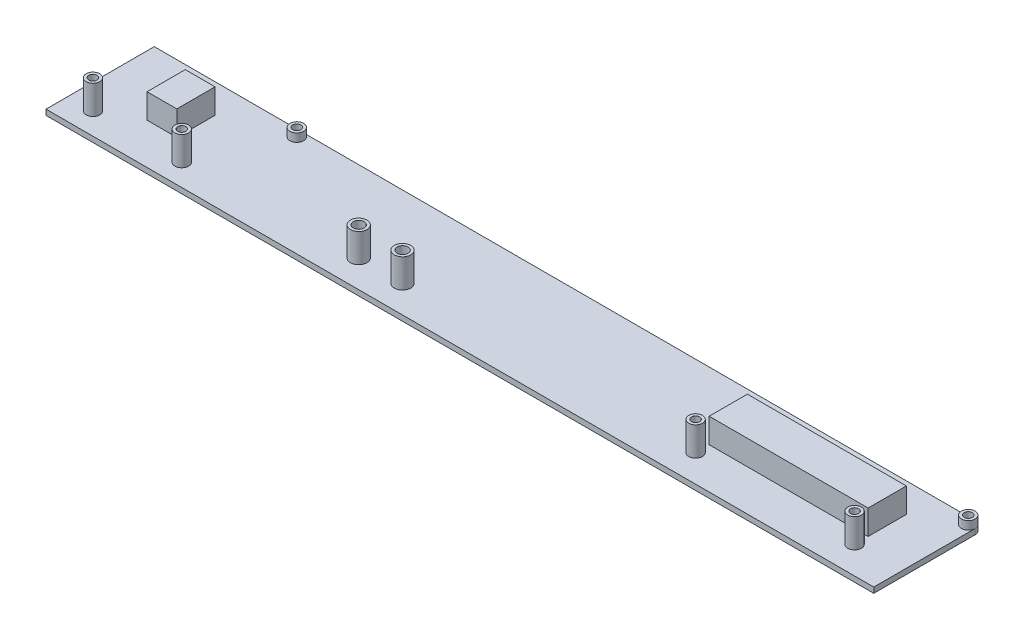
SolidWorks part; units mm, degrees
ref_plane "前视基准面" through (0, 0, 0) normal (0, 0, 1) x (1, 0, 0)
ref_plane "上视基准面" through (0, 0, 0) normal (0, 1, 0) x (1, 0, 0)
ref_plane "右视基准面" through (0, 0, 0) normal (1, 0, 0) x (0, 0, -1)
sketch "草图1" plane through (0, 0, 0) normal (0, 1, 0) x (1, 0, 0)
  line L1 (-209.4292, 16.4491) -> (40.5708, 16.4491)
  line L2 (-209.4292, 16.4491) -> (-209.4292, -23.0509)
  line L3 (-209.4292, -23.0509) -> (40.5708, -23.0509)
  line L4 (40.5708, 16.4491) -> (40.5708, -23.0509)
  dimension "D1" = 250
  dimension "D2" = 39.5
extrude "凸台-拉伸1" add sketch "草图1" along normal blind 2 contours L1 L4 L3 L2
sketch "草图2" plane through (0, 2, 0) normal (0, 1, 0) x (1, 0, 0)
  line L1 (-209.4292, 16.4491) -> (40.5708, 16.4491) construction
  line L2 (40.5708, 16.4491) -> (40.5708, -23.0509) construction
  circle A0 centre (38.0708, 13.9491) radius 2.5
  circle A1 centre (38.0708, 13.9491) radius 1.5
  dimension "D1" = 5
  dimension "D2" = 2.5
  dimension "D3" = 2.5
  dimension "D4" = 3
extrude "凸台-拉伸2" add sketch "草图2" along normal blind 3
fillet "圆角1" radius 2.5 1 edges at (40.5708, 1, -16.4491)
sketch "草图6" plane through (0, 2, 0) normal (0, 1, 0) x (1, 0, 0)
  line L0 (-209.4292, 16.4491) -> (38.0708, 16.4491) construction
  line L1 (-209.4292, 16.4491) -> (-209.4292, -23.0509) construction
  circle A0 centre (-206.9292, 13.9491) radius 2.5
  circle A1 centre (-206.9292, 13.9491) radius 1.5
  dimension "D1" = 5
  dimension "D2" = 2.5
  dimension "D3" = 2.5
  dimension "D4" = 3
extrude "凸台-拉伸3" add sketch "草图6" along normal blind 3
sketch "草图7" plane through (0, 2, 0) normal (0, 1, 0) x (1, 0, 0)
  circle A0 centre (38.0708, 13.9491) radius 1.5
  circle A1 centre (38.0708, 13.9491) radius 1.5 construction
  dimension "D2" = 3
  dimension "D1" = 0
extrude "切除-拉伸1" cut sketch "草图7" against normal blind 1
sketch "草图8" plane through (0, 2, 0) normal (0, 1, 0) x (1, 0, 0)
  circle A0 centre (-206.9292, 13.9491) radius 1.5
  circle A1 centre (-206.9292, 13.9491) radius 1.5 construction
  dimension "D2" = 3
  dimension "D1" = 0
extrude "切除-拉伸2" cut sketch "草图8" against normal blind 1
sketch "草图9" plane through (0, 2, 0) normal (0, 1, 0) x (1, 0, 0)
  line L0 (-209.4292, -23.0509) -> (40.5708, -23.0509) construction
  line L1 (40.5708, 13.9491) -> (40.5708, -23.0509) construction
  circle A0 centre (23.5708, -13.0509) radius 2.5
  circle A1 centre (23.5708, -13.0509) radius 1.5
  circle A2 centre (-34.4292, -13.0509) radius 2.5
  circle A3 centre (-34.4292, -13.0509) radius 1.5
  dimension "D1" = 5
  dimension "D2" = 3
  dimension "D5" = 5
  dimension "D6" = 3
  dimension "D3" = 10
  dimension "D4" = 17
  dimension "D7" = 10
  dimension "D8" = 58
extrude "凸台-拉伸5" add sketch "草图9" along normal blind 10.5
sketch "草图10" plane through (-209.4292, 0, 0) normal (-1, 0, 0) x (0, 0, 1)
  line L1 (-16.4491, 2) -> (23.0509, 2)
  line L2 (-16.4491, 2) -> (-16.4491, 0)
  line L3 (-16.4491, 0) -> (23.0509, 0)
  line L4 (23.0509, 2) -> (23.0509, 0)
extrude "凸台-拉伸6" add sketch "草图10" along normal blind 52
sketch "草图11" plane through (0, 2, 0) normal (0, 1, 0) x (1, 0, 0)
  line L0 (-261.4292, -23.0509) -> (40.5708, -23.0509) construction
  circle A0 centre (-252.2996, -15.0509) radius 1.5
  circle A1 centre (-252.2996, -15.0509) radius 2.5
  circle A2 centre (-219.8996, -15.0509) radius 2.5
  circle A3 centre (-219.8996, -15.0509) radius 1.5
  point P6 (0, 0)
  point P7 (0, 0)
  point P8 (-204.1347, -20.63)
  point P9 (-219.9913, -23.0509)
  dimension "D1" = 3
  dimension "D2" = 5
  dimension "D3" = 3
  dimension "D4" = 5
  dimension "D5" = 8
  dimension "D6" = 8
extrude "凸台-拉伸7" add sketch "草图11" along normal blind 10.5
sketch "草图13" plane through (0, 2, 0) normal (0, 1, 0) x (1, 0, 0)
  line L1 (-34.4292, 5.8421) -> (23.5708, 5.8421)
  line L2 (-34.4292, 5.8421) -> (-34.4292, -8.1077)
  line L3 (-34.4292, -8.1077) -> (23.5708, -8.1077)
  line L4 (23.5708, 5.8421) -> (23.5708, -8.1077)
  line L5 (-239.5068, 5.8421) -> (-228.6398, 5.8421)
  line L6 (-239.5068, 5.8421) -> (-239.5068, -8.1077)
  line L7 (-239.5068, -8.1077) -> (-228.6398, -8.1077)
  line L8 (-228.6398, 5.8421) -> (-228.6398, -8.1077)
extrude "凸台-拉伸8" add sketch "草图13" along normal blind 9
sketch "草图14" plane through (0, 2, 0) normal (0, 1, 0) x (1, 0, 0)
  line L0 (-261.4292, -23.0509) -> (40.5708, -23.0509) construction
  circle A0 centre (-157.3417, -13.0509) radius 2
  circle A1 centre (-141.3417, -13.0509) radius 2
  circle A2 centre (-141.3417, -13.0509) radius 3
  circle A3 centre (-157.3417, -13.0509) radius 3
  dimension "D1" = 4
  dimension "D2" = 6
  dimension "D3" = 4
  dimension "D4" = 6
  dimension "D5" = 16
  dimension "D6" = 10
extrude "凸台-拉伸9" add sketch "草图14" along normal blind 10.5
